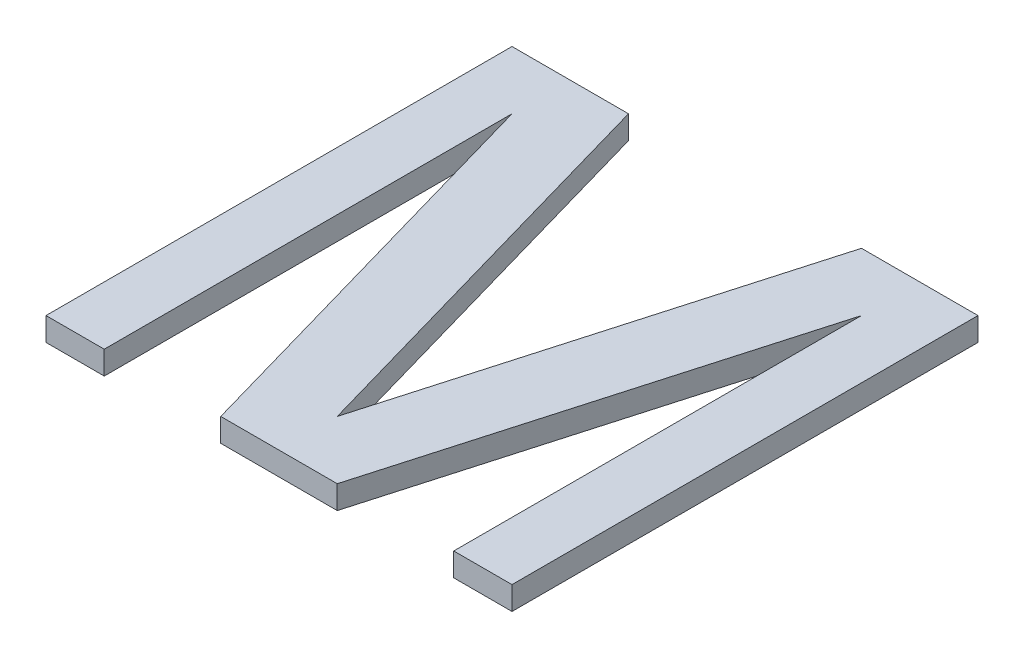
SolidWorks part; units mm, degrees
ref_plane "Front Plane" through (0, 0, 0) normal (0, 0, 1) x (1, 0, 0)
ref_plane "Top Plane" through (0, 0, 0) normal (0, 1, 0) x (1, 0, 0)
ref_plane "Right Plane" through (0, 0, 0) normal (1, 0, 0) x (0, 0, -1)
sketch "Sketch1" plane through (0, 0, 0) normal (0, 1, 0) x (1, 0, 0)
  line L0 (-19.1468, 16.6938) -> (-9.1468, 16.6938)
  line L2 (-19.1468, 16.6938) -> (-19.1468, -23.3062)
  line L3 (-19.1468, -23.3062) -> (-14.1468, -23.3062)
  line L4 (20.8532, 16.6938) -> (20.8532, -23.3062)
  line L5 (-14.1468, 11.6938) -> (-4.1468, -23.3062)
  line L6 (-14.1468, -18.3062) -> (15.8532, -18.3062) construction
  line L7 (20.8532, 16.6938) -> (10.8532, 16.6938)
  line L8 (-4.1468, -23.3062) -> (5.8532, -23.3062)
  line L9 (-19.1468, -23.3062) -> (20.8532, -23.3062) construction
  line L11 (-14.1468, 11.6938) -> (-14.1468, -18.3062)
  line L13 (15.8532, 11.6938) -> (15.8532, -18.3062)
  line L14 (-14.1468, -18.3062) -> (-14.1468, -23.3062)
  line L15 (15.8532, -18.3062) -> (15.8532, -23.3062)
  line L16 (15.8532, -23.3062) -> (20.8532, -23.3062)
  line L18 (-14.1468, 16.6938) -> (-14.1468, -18.3062) construction
  line L19 (15.8532, 16.6938) -> (15.8532, -18.3062) construction
  line L21 (15.8532, 11.6938) -> (5.8532, -23.3062)
  line L25 (-9.1468, 16.6938) -> (0.8532, -18.3062)
  line L26 (0.8532, -18.3062) -> (10.8532, 16.6938)
  point P0 (0, 0)
  point P13 (0.8532, -23.3062)
extrude "Boss-Extrude2" add sketch "Sketch1" along normal blind 2
